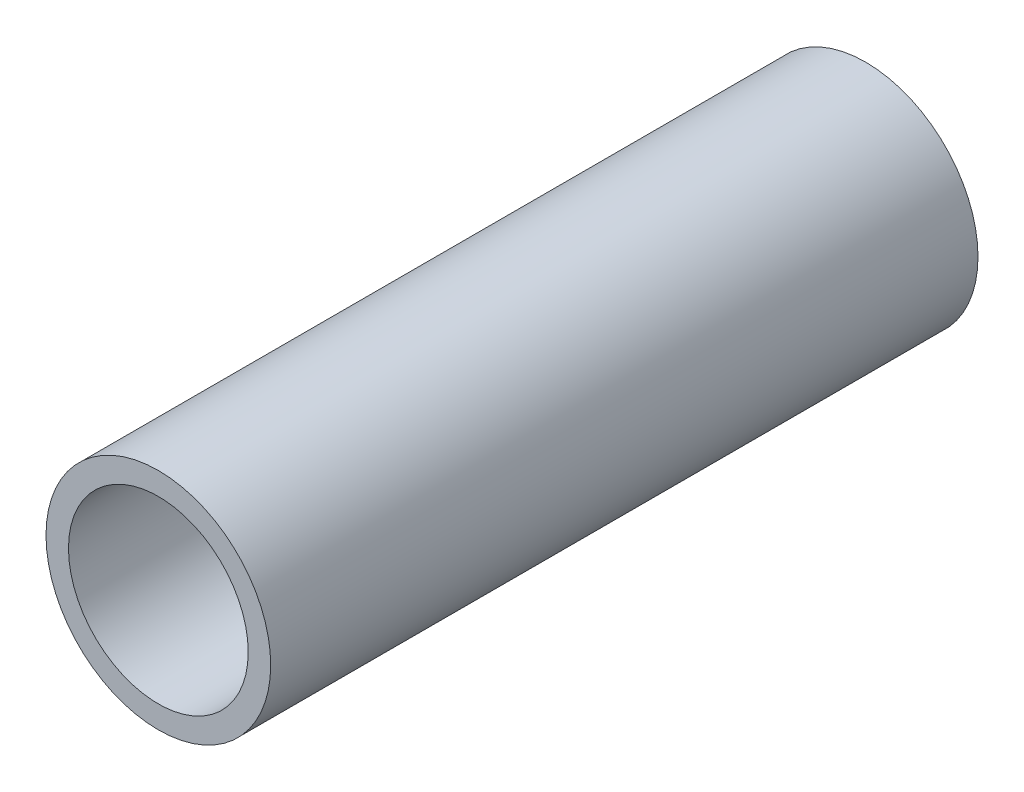
SolidWorks part; units mm, degrees
ref_plane "Front Plane" through (0, 0, 0) normal (0, 0, 1) x (1, 0, 0)
ref_plane "Top Plane" through (0, 0, 0) normal (0, 1, 0) x (1, 0, 0)
ref_plane "Right Plane" through (0, 0, 0) normal (1, 0, 0) x (0, 0, -1)
sketch "Sketch1" plane through (0, 0, 0) normal (0, 0, 1) x (1, 0, 0)
  circle A0 centre (0, 0) radius 0.635
  circle A1 centre (0, 0) radius 0.508
extrude "Extrude1" add sketch "Sketch1" along normal blind 3.998
